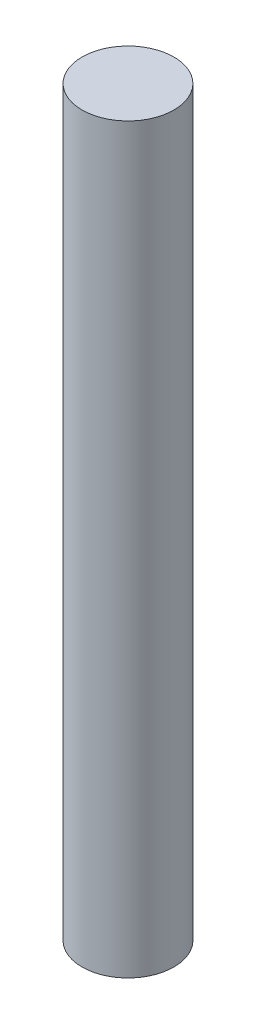
SolidWorks part; units mm, degrees
ref_plane "Front Plane" through (0, 0, 0) normal (0, 0, 1) x (1, 0, 0)
ref_plane "Top Plane" through (0, 0, 0) normal (0, 1, 0) x (1, 0, 0)
ref_plane "Right Plane" through (0, 0, 0) normal (1, 0, 0) x (0, 0, -1)
sketch "Sketch1" plane through (0, 0, 0) normal (0, 1, 0) x (1, 0, 0)
  circle A0 centre (0, 0) radius 6.2865
  dimension "D1" = 12.573
extrude "Boss-Extrude1" add sketch "Sketch1" along normal blind 101.6 contours A0
